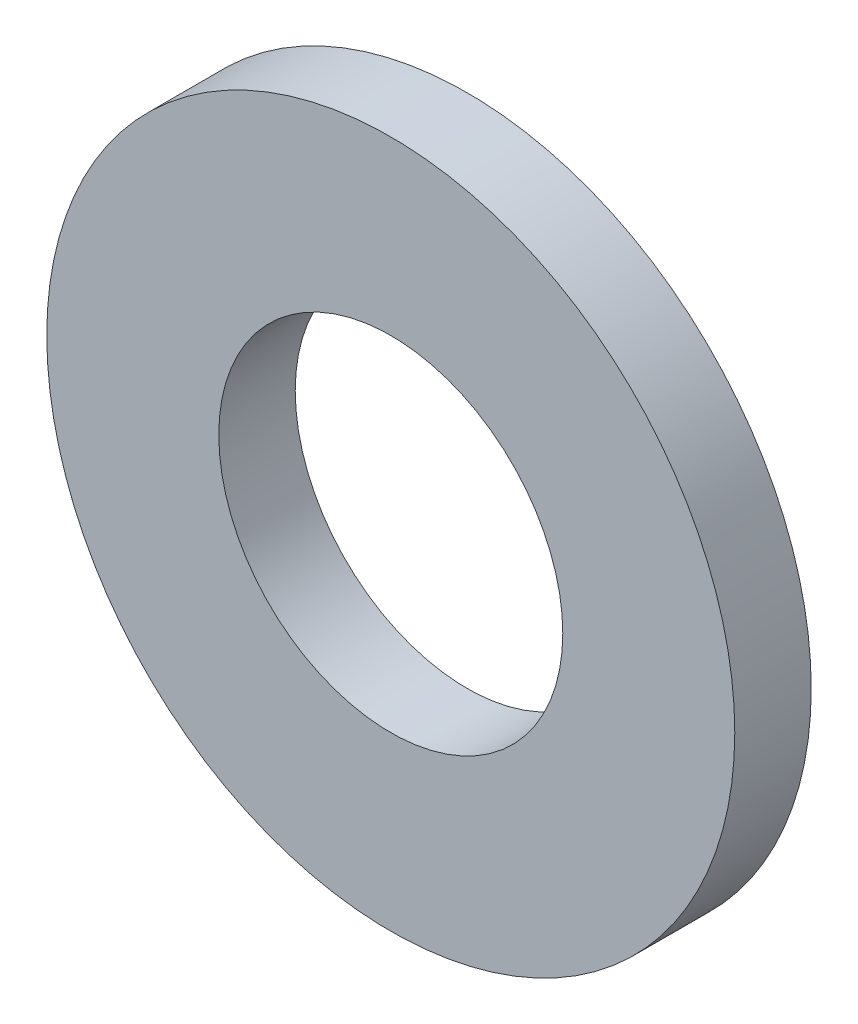
SolidWorks part; units mm, degrees
ref_plane "前基準面" through (0, 0, 0) normal (0, 0, 1) x (1, 0, 0)
ref_plane "上基準面" through (0, 0, 0) normal (0, 1, 0) x (1, 0, 0)
ref_plane "右基準面" through (0, 0, 0) normal (1, 0, 0) x (0, 0, -1)
sketch "草圖1" plane through (0, 0, 0) normal (0, 0, 1) x (1, 0, 0)
  circle A0 centre (0, 0) radius 2.25
  circle A1 centre (0, 0) radius 4.5
  dimension "D1" = 4.5
  dimension "D2" = 9
extrude "填料-伸長1" add sketch "草圖1" along normal blind 1
